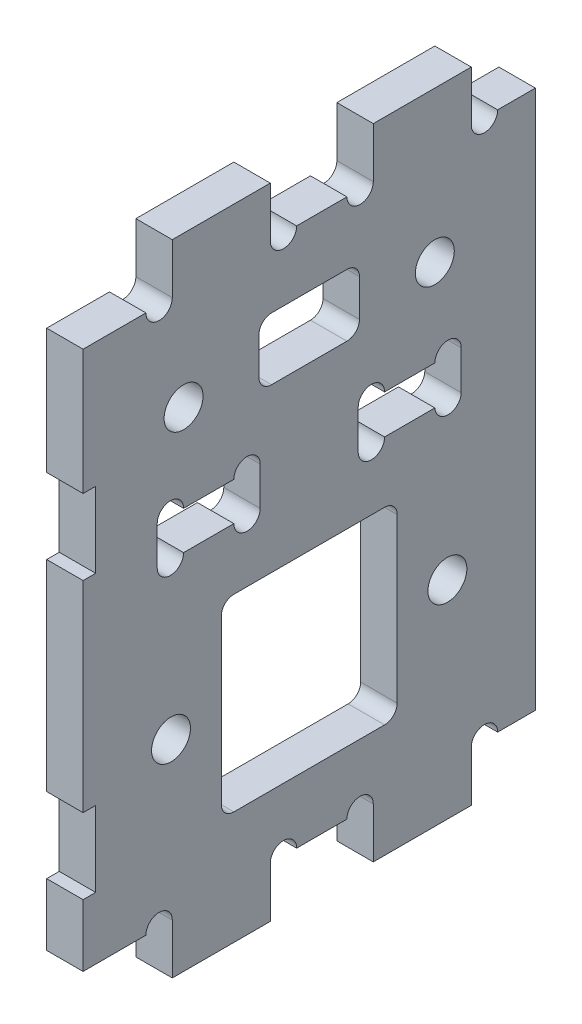
SolidWorks part; units mm, degrees
material "Thornel Mat VMA"
ref_plane "前视基准面" through (0, 0, 0) normal (0, 0, 1) x (1, 0, 0)
ref_plane "上视基准面" through (0, 0, 0) normal (0, 1, 0) x (1, 0, 0)
ref_plane "右视基准面" through (0, 0, 0) normal (1, 0, 0) x (0, 0, -1)
sketch "草图1" plane through (0, 0, 0) normal (1, 0, 0) x (0, 0, -1)
  line L0 (-10.9, 21.45) -> (-10.9, 25.45)
  line L1 (18, -21.45) -> (12.9, -21.45)
  line L2 (18, -21.45) -> (18, 21.45)
  line L3 (18, 21.45) -> (12.9, 21.45)
  line L4 (-18, -21.45) -> (-18, -16.95)
  line L5 (18, -21.45) -> (-18, 21.45) construction
  line L6 (18, 21.45) -> (-18, -21.45) construction
  line L7 (-10.9, 25.45) -> (-3.1, 25.45)
  line L8 (-3.1, 25.45) -> (-3.1, 21.45)
  line L9 (5.1, 21.45) -> (5.1, 25.45)
  line L10 (5.1, 25.45) -> (12.9, 25.45)
  line L11 (12.9, 25.45) -> (12.9, 21.45)
  line L12 (-7, 25.45) -> (-7, 16.2138) construction
  line L13 (9, 25.45) -> (9, 16.2138) construction
  line L14 (-10.9, 21.45) -> (-18, 21.45)
  line L15 (5.1, 21.45) -> (-3.1, 21.45)
  line L16 (-17, 0) -> (-8, 0) construction
  line L17 (9, -25.45) -> (9, -16.2138) construction
  line L18 (-7, -25.45) -> (-7, -16.2138) construction
  line L19 (5.1, -21.45) -> (-3.1, -21.45)
  line L20 (12.9, -25.45) -> (12.9, -21.45)
  line L21 (5.1, -25.45) -> (12.9, -25.45)
  line L22 (5.1, -21.45) -> (5.1, -25.45)
  line L23 (-3.1, -25.45) -> (-3.1, -21.45)
  line L24 (-10.9, -25.45) -> (-3.1, -25.45)
  line L25 (-10.9, -21.45) -> (-10.9, -25.45)
  line L26 (-10.9, -21.45) -> (-18, -21.45)
  line L27 (5.1, -21.45) -> (-3.1, -21.45)
  line L28 (-18, -8.95) -> (18.7225, -8.95) construction
  line L29 (-18, -16.95) -> (-15, -16.95) construction
  line L30 (7, -1.45) -> (-7, -1.45)
  line L31 (7, -1.45) -> (7, -16.45)
  line L32 (7, -16.45) -> (-7, -16.45)
  line L33 (-7, -1.45) -> (-7, -16.45)
  line L34 (7, -1.45) -> (-7, -16.45) construction
  line L35 (7, -16.45) -> (-7, -1.45) construction
  line L36 (-15, -16.95) -> (-15, -11.95) construction
  line L37 (-15, -11.95) -> (-18, -11.95) construction
  line L38 (-15, -14.45) -> (-18.1995, -14.45) construction
  line L39 (0, 0) -> (-13.05, 0) construction
  line L40 (-15, 11.95) -> (-18, 11.95) construction
  line L41 (-15, 16.95) -> (-15, 11.95) construction
  line L42 (-18, 16.95) -> (-15, 16.95) construction
  line L43 (-18, -11.95) -> (-18, 11.95)
  line L44 (-18, 16.95) -> (-18, 21.45)
  line L45 (1, 21.45) -> (1, 10.75) construction
  line L46 (-18, 16.95) -> (-18, 11.95)
  line L47 (-18, -11.95) -> (-18, -16.95)
  circle A0 centre (-11.95, 21.45) radius 1.05
  circle A1 centre (-2.05, 21.45) radius 1.05
  circle A2 centre (4.05, 21.45) radius 1.05
  circle A3 centre (13.95, 21.45) radius 1.05
  circle A4 centre (13.95, -21.45) radius 1.05
  circle A5 centre (4.05, -21.45) radius 1.05
  circle A6 centre (-2.05, -21.45) radius 1.05
  circle A7 centre (-11.95, -21.45) radius 1.05
  circle A8 centre (-11, -8.95) radius 1.55
  circle A9 centre (11, -8.95) radius 1.55
  point P0 (0, 0)
  point P54 (0, -8.95)
  dimension "D7" = 2.1
  dimension "D8" = 3.1
  dimension "D1" = 42.9
  dimension "D2" = 4
  dimension "D3" = 11
  dimension "D4" = 7.8
  dimension "D5" = 36
  dimension "D6" = 8
  dimension "D9" = 7
  dimension "D10" = 7
  dimension "D11" = 12.5
  dimension "D12" = 5
  dimension "D13" = 4
  dimension "D14" = 4
  dimension "D15" = 7
  dimension "D16" = 5
  dimension "D17" = 3
extrude "凸台-拉伸1" add sketch "草图1" along normal blind 2.9 contours L26 A7 L25 L24 L23 A6 L27 A5 L22 L21 L20 A4 L1 L2 L3 A3 L11 L10 L9 A2 L15 A1 L8 L7 L0 A0 L14 L4 A9 A8
sketch "草图2" plane through (2.9, 0, 0) normal (1, 0, 0) x (0, 0, -1)
  line L0 (3, -21.45) -> (-1, -21.45) construction
  line L1 (0, 0) -> (0, 15.7902) construction
  line L8 (12.05, 3.45) -> (12.05, 6.45) construction
  line L9 (3.95, 3.45) -> (3.95, 6.45) construction
  line L10 (12.05, 6.45) -> (3.95, 6.45) construction
  line L11 (12.05, 3.45) -> (3.95, 3.45) construction
  line L12 (-12.05, 3.475) -> (-12.05, 6.425) construction
  line L13 (-3.95, 6.425) -> (-12.05, 6.425) construction
  line L14 (-3.95, 3.475) -> (-3.95, 6.425) construction
  line L15 (-3.95, 3.475) -> (-12.05, 3.475) construction
  line L16 (-12.1, 3.425) -> (-12.1, 6.475)
  line L17 (-6, 6.475) -> (-10, 6.475)
  line L18 (-3.9, 3.425) -> (-3.9, 6.475)
  line L19 (-6, 3.425) -> (-10, 3.425)
  line L20 (12.1, 3.4) -> (12.1, 6.5)
  line L21 (10, 6.5) -> (6, 6.5)
  line L22 (3.9, 3.4) -> (3.9, 6.5)
  line L23 (10.0024, 3.4) -> (6, 3.4)
  line L25 (-3.9, 6.475) -> (-12.1, 6.475) construction
  line L26 (-3.9, 3.425) -> (-12.1, 3.425) construction
  line L27 (12.1, 3.4) -> (3.9, 3.4) construction
  line L28 (12.1, 6.5) -> (3.9, 6.5) construction
  line L36 (3.9, 4.95) -> (-3.9, 4.95) construction
  line L37 (3, 21.45) -> (-1, 21.45) construction
  line L38 (-8, 6.475) -> (-8, 0.4388) construction
  line L43 (-18, -21.45) -> (-18, 21.45) construction
  line L44 (8, 6.45) -> (8, 2.7334) construction
  line L45 (-4, 11.5) -> (4, 11.5)
  line L46 (-25, 5.5) -> (-17, 5.5)
  line L47 (-25, 5.5) -> (-25, 11.5)
  line L48 (-25, 11.5) -> (-17, 11.5)
  line L49 (-17, 5.5) -> (-17, 11.5)
  line L50 (-25, 5.5) -> (-17, 11.5) construction
  line L51 (-25, 11.5) -> (-17, 5.5) construction
  line L52 (-25, -16.5) -> (-17, -16.5)
  line L53 (-17, -10.5) -> (-17, -16.5)
  line L54 (-25, -10.5) -> (-25, -16.5)
  line L55 (-25, -10.5) -> (-17, -10.5)
  line L56 (-25, -13.5) -> (-17, -13.5) construction
  line L57 (-4, 11.5) -> (-4, 16.45)
  line L58 (-4, 16.45) -> (4, 16.45)
  line L59 (4, 11.5) -> (4, 16.45)
  line L60 (-4, 11.5) -> (4, 16.45) construction
  line L61 (-4, 16.45) -> (4, 11.5) construction
  line L62 (0, 0) -> (0, -10.9473) construction
  arc A0 (-12.1, 3.425) -> (-10, 3.425) centre (-11.05, 3.425) ccw
  arc A1 (-10, 6.475) -> (-12.1, 6.475) centre (-11.05, 6.475) ccw
  arc A2 (-3.9, 6.475) -> (-6, 6.475) centre (-4.95, 6.475) ccw
  arc A3 (-6, 3.425) -> (-3.9, 3.425) centre (-4.95, 3.425) ccw
  arc A4 (3.9, 3.4) -> (6, 3.4) centre (4.95, 3.4) ccw
  arc A5 (6, 6.5) -> (3.9, 6.5) centre (4.95, 6.5) ccw
  arc A6 (12.1, 6.5) -> (10, 6.5) centre (11.05, 6.5) ccw
  arc A7 (10.0024, 3.4) -> (12.1, 3.4) centre (11.0512, 3.45) ccw
  circle A8 centre (10, 13.45) radius 1.55
  circle A9 centre (-10, 13.45) radius 1.55
  point P31 (0, 13.975)
  point P53 (-21, 8.5)
  dimension "D3" = 2.1
  dimension "D6" = 3.1
  dimension "D4" = 8
  dimension "D5" = 20
  dimension "D7" = 5
  dimension "D8" = 13.5
  dimension "D9" = 6
  dimension "D10" = 26.4
  dimension "D11" = 16
  dimension "D12" = 3.1
  dimension "D14" = 3.05
  dimension "D15" = 8.2
  dimension "D16" = 8.2
  dimension "D17" = 8
  dimension "D18" = 1
  dimension "D19" = 22
  dimension "D20" = 5
  dimension "D21" = 6
  dimension "D1" = 0.05
  dimension "D2" = 0.05
extrude "切除-拉伸1" cut sketch "草图2" against normal blind 10
fillet "圆角1" radius 1 8 edges at (1.45, -16.45, 7) (1.45, -16.45, -7) (1.45, -1.45, 7) (1.45, -1.45, -7) (1.45, 11.5, 4) (1.45, 16.45, 4) (1.45, 11.5, -4) (1.45, 16.45, -4)
